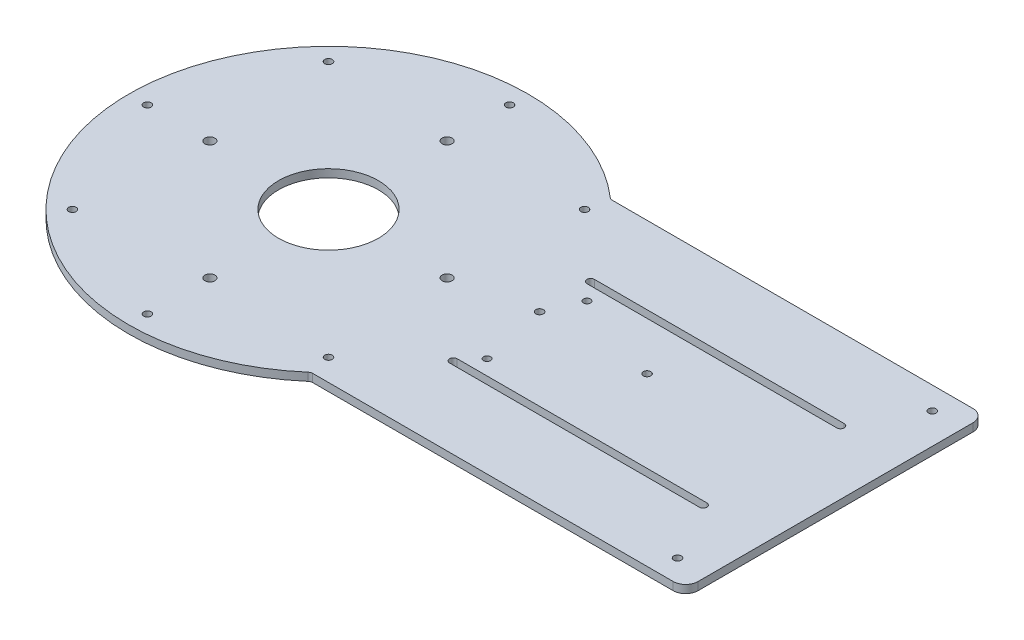
SolidWorks part; units mm, degrees
ref_plane "Front Plane" through (0, 0, 0) normal (0, 0, 1) x (1, 0, 0)
ref_plane "Top Plane" through (0, 0, 0) normal (0, 1, 0) x (1, 0, 0)
ref_plane "Right Plane" through (0, 0, 0) normal (1, 0, 0) x (0, 0, -1)
sketch "Sketch1" plane through (0, 0, 0) normal (0, 1, 0) x (1, 0, 0)
  line L0 (0, 0) -> (283, 0) construction
  line L1 (283, 0) -> (283, 60) construction
  line L2 (283, 0) -> (283, -60) construction
  line L3 (283, 55) -> (283, -55)
  line L4 (0, 0) -> (80, 0) construction
  line L5 (278, 60) -> (133.6656, 60)
  line L6 (278, -60) -> (133.6656, -60)
  line L10 (283, 60) -> (270.75, 60) construction
  line L11 (270.75, 60) -> (270.75, 51) construction
  line L12 (257.5, -27.5) -> (133.6656, -27.5) construction
  line L13 (257.5, 27.5) -> (133.6656, 27.5) construction
  line L15 (250.5, 27.5) -> (250.5, -27.5) construction
  line L16 (257.5, 34.5) -> (257.5, -34.5) construction
  line L19 (257.5, -34.5) -> (133.6656, -34.5) construction
  line L20 (257.5, 34.5) -> (133.6656, 34.5) construction
  line L21 (250.5, -27.5) -> (133.6656, -27.5) construction
  line L22 (250.5, 27.5) -> (133.6656, 27.5) construction
  line L23 (257.5, -27.5) -> (157.5, -27.5) construction
  line L24 (257.5, 27.5) -> (157.5, 27.5) construction
  line L25 (157.5, -29) -> (257.5, -29)
  line L26 (157.5, -26) -> (257.5, -26)
  line L27 (257.5, 26) -> (157.5, 26)
  line L28 (257.5, 29) -> (157.5, 29)
  line L29 (283, 60) -> (283, 20) construction
  line L30 (283, 20) -> (163.5, 20) construction
  line L31 (283, -60) -> (283, 6.8) construction
  line L32 (283, 6.8) -> (157.75, 6.8) construction
  line L33 (157.75, 6.8) -> (200.75, 6.8) construction
  arc A0 (132.3567, 60.4878) -> (132.3567, -60.4878) centre (80, 0) ccw
  circle A1 centre (80, 0) radius 20
  arc A2 (133.6656, -60) -> (132.3567, -60.4878) centre (133.6656, -62) ccw
  arc A3 (133.6656, 60) -> (132.3567, 60.4878) centre (133.6656, 62) cw
  circle A7 centre (7.5, 0) radius 1.5
  circle A8 centre (28.7348, 51.2652) radius 1.5
  circle A9 centre (80, 72.5) radius 1.5
  circle A10 centre (131.2652, 51.2652) radius 1.5
  circle A12 centre (131.2652, -51.2652) radius 1.5
  circle A13 centre (80, -72.5) radius 1.5
  circle A14 centre (28.7348, -51.2652) radius 1.5
  circle A15 centre (152.5, 0) radius 1.5 [skipped]
  circle A16 centre (80, 0) radius 47.5 construction
  circle A17 centre (32.5, 0) radius 2
  circle A18 centre (80, 47.5) radius 2
  circle A19 centre (127.5, 0) radius 2
  circle A20 centre (80, -47.5) radius 2
  circle A21 centre (270.75, 51) radius 1.5
  circle A22 centre (270.75, -51) radius 1.5
  arc A23 (283, -55) -> (278, -60) centre (278, -55) cw
  arc A24 (283, 55) -> (278, 60) centre (278, 55) ccw
  arc A28 (250.5, 27.5) -> (250.5, 27.5) centre (250.5, 27.5) ccw
  arc A29 (250.5, -27.5) -> (250.5, -27.5) centre (250.5, -27.5) cw
  arc A30 (133.6656, -27.5) -> (111.0868, -35.9146) centre (133.6656, -62) ccw construction
  arc A31 (111.0868, 35.9146) -> (111.0868, -35.9146) centre (80, 0) ccw construction
  arc A32 (133.6656, 27.5) -> (111.0868, 35.9146) centre (133.6656, 62) cw construction
  arc A33 (257.5, -34.5) -> (257.5, -34.5) centre (257.5, -34.5) cw
  arc A37 (257.5, 34.5) -> (257.5, 34.5) centre (257.5, 34.5) ccw
  arc A38 (133.6656, -34.5) -> (115.668, -41.2073) centre (133.6656, -62) ccw construction
  arc A39 (115.668, 41.2073) -> (115.668, -41.2073) centre (80, 0) ccw construction
  arc A40 (133.6656, 34.5) -> (115.668, 41.2073) centre (133.6656, 62) cw construction
  arc A41 (257.5, -29) -> (257.5, -26) centre (257.5, -27.5) ccw
  arc A42 (257.5, 26) -> (257.5, 29) centre (257.5, 27.5) ccw
  arc A43 (157.5, -26) -> (157.5, -29) centre (157.5, -27.5) ccw
  arc A44 (157.5, 29) -> (157.5, 26) centre (157.5, 27.5) ccw
  circle A45 centre (163.5, 20) radius 1.4
  circle A46 centre (163.5, -20) radius 1.4
  circle A47 centre (157.75, 6.8) radius 1.5
  circle A48 centre (200.75, 6.8) radius 1.5
  point P32 (80, 0)
  point P42 (80, 0)
  dimension "D5" = 2
  dimension "D7" = 8
  dimension "D8" = 4
  dimension "D9" = 9
  dimension "D11" = 5
  dimension "D16" = 100
  dimension "D19" = 119.5
  dimension "D22" = 43
  dimension "D1" = 283
  dimension "D2" = 60
  dimension "D3" = 60
  dimension "D4" = 80
  dimension "D6" = 7.5
  dimension "D10" = 12.25
  dimension "D13" = 32.5
  dimension "D15" = 25.5
  dimension "D17" = 100
  dimension "D18" = 40
  dimension "D20" = 53.2
  dimension "D21" = 125.25
  dimension "D12" = 32.5
  dimension "D14" = 25.5
extrude "Boss-Extrude1" add sketch "Sketch1" along normal blind 3.2 contours L3 A24 L5 A3 A0 A2 L6 A23 A48 A47 A1 A7 A8 A9 A10 A12 A13 A14 A17 A18 A19 A20 A21 A22 A43 L26 A41 L25 A44 L28 A42 L27
